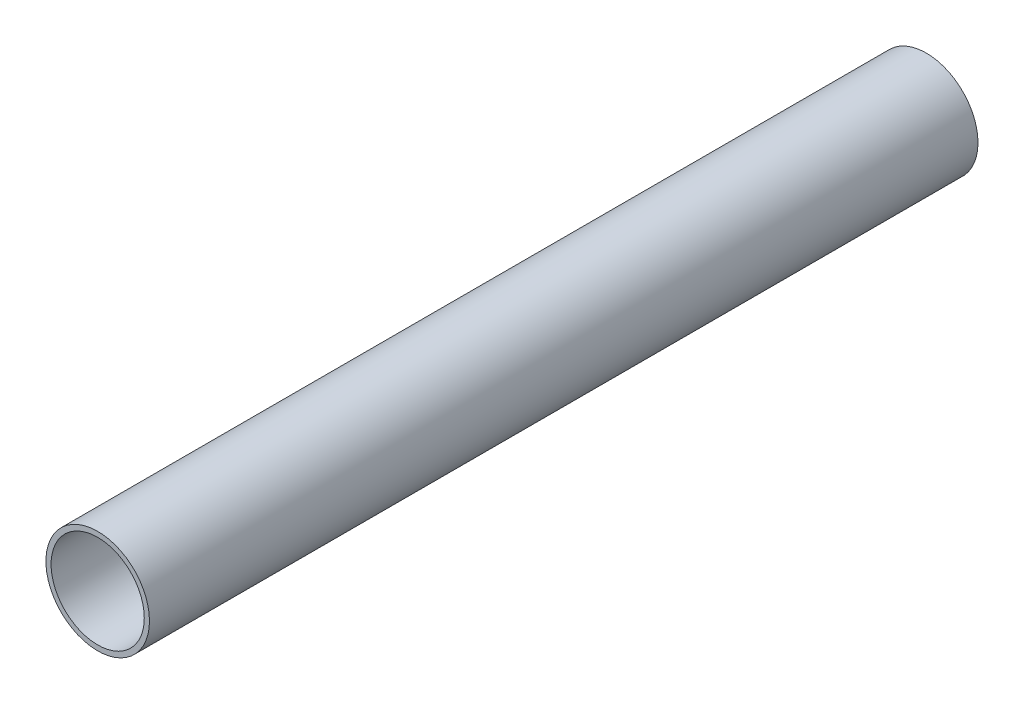
SolidWorks part; units mm, degrees
material "Alliage 1060"
ref_plane "Plan de face" through (0, 0, 0) normal (0, 0, 1) x (1, 0, 0)
ref_plane "Plan de dessus" through (0, 0, 0) normal (0, 1, 0) x (1, 0, 0)
ref_plane "Plan de droite" through (0, 0, 0) normal (1, 0, 0) x (0, 0, -1)
sketch "Esquisse1" plane through (0, 0, 0) normal (0, 0, 1) x (1, 0, 0)
  circle A0 centre (0, 0) radius 10
  dimension "D1" = 20
extrude "Boss.-Extru.1" add sketch "Esquisse1" along normal blind 160
sketch "Esquisse2" plane through (0, 0, 160) normal (0, 0, 1) x (1, 0, 0)
  circle A0 centre (0, 0) radius 9
  dimension "D1" = 18
extrude "Enlèv. mat.-Extru.1" cut sketch "Esquisse2" against normal through all
